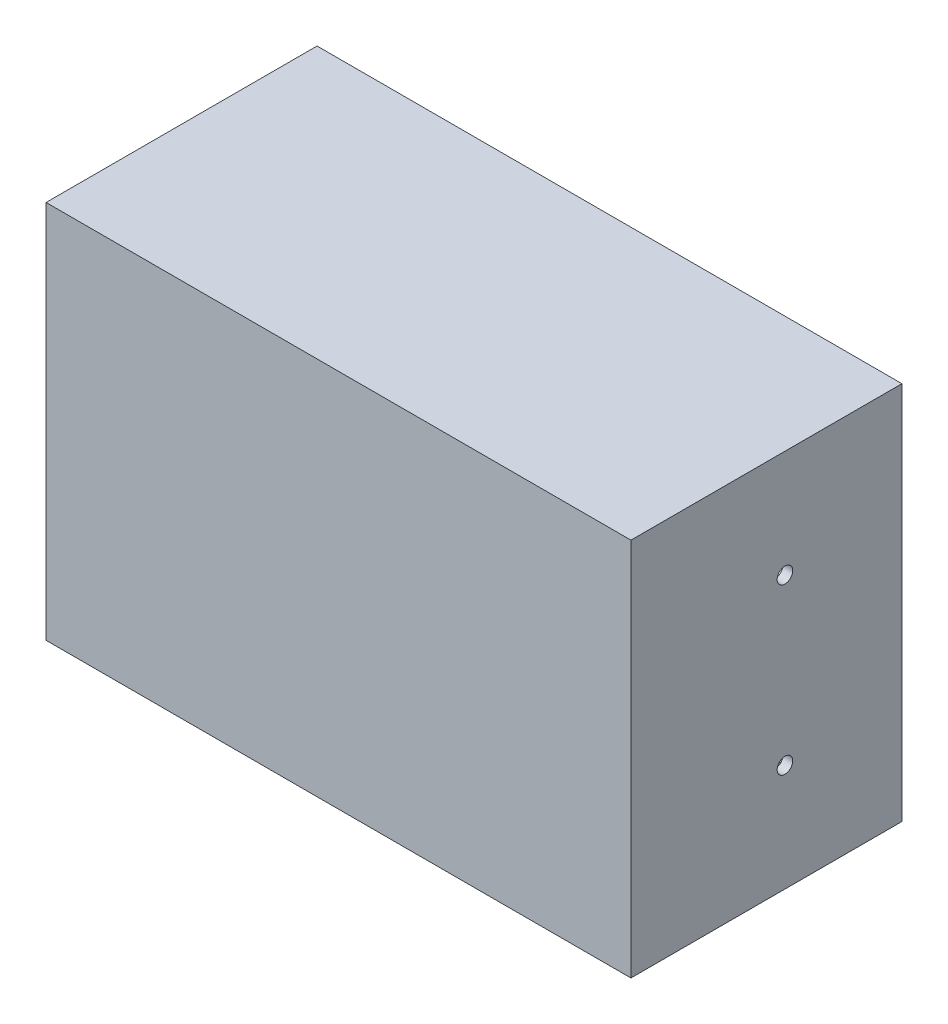
SolidWorks part; units mm, degrees
ref_plane "Ebene vorne" through (0, 0, 0) normal (0, 0, 1) x (1, 0, 0)
ref_plane "Ebene oben" through (0, 0, 0) normal (0, 1, 0) x (1, 0, 0)
ref_plane "Ebene rechts" through (0, 0, 0) normal (1, 0, 0) x (0, 0, -1)
sketch "Skizze1" plane through (0, 0, 0) normal (0, 0, 1) x (1, 0, 0)
  line L1 (-150, -97.25) -> (150, -97.25)
  line L2 (-150, -97.25) -> (-150, 97.25)
  line L3 (-150, 97.25) -> (150, 97.25)
  line L4 (150, -97.25) -> (150, 97.25)
  line L5 (-150, -97.25) -> (150, 97.25) construction
  line L6 (-150, 97.25) -> (150, -97.25) construction
  point P0 (0, 0)
  dimension "D1" = 194.5
  dimension "D2" = 300
extrude "Aufsatz-Linear austragen1" add sketch "Skizze1" along normal blind 139 contours L3 L4 L1 L2
sketch "Skizze2" plane through (0, 0, 0) normal (0, 0, -1) x (-1, 0, 0)
  line L0 (150, 97.25) -> (-150, 97.25) construction
  line L1 (-145, 92.25) -> (145, 92.25)
  line L2 (-145, 92.25) -> (-145, -92.25)
  line L3 (-145, -92.25) -> (145, -92.25)
  line L4 (145, 92.25) -> (145, -92.25)
  line L5 (-145, 92.25) -> (145, -92.25) construction
  line L6 (-145, -92.25) -> (145, 92.25) construction
  line L7 (150, -97.25) -> (150, 97.25) construction
  line L8 (150, -97.25) -> (-150, -97.25) construction
  line L9 (-150, -97.25) -> (-150, 97.25) construction
  point P0 (0, 0)
  dimension "D1" = 5
  dimension "D2" = 5
  dimension "D3" = 5
  dimension "D4" = 5
extrude "Schnitt-Linear austragen1" cut sketch "Skizze2" against normal blind 134 contours L3 L4 L1 L2
sketch "Skizze5" plane through (-150, 0, 0) normal (-1, 0, 0) x (0, 0, 1)
  line L0 (0, -97.25) -> (0, 97.25) construction
  line L1 (139, -97.25) -> (0, -97.25) construction
  circle A0 centre (60, -42.25) radius 28.2128
  dimension "D1" = 60
  dimension "D2" = 55
ref_plane "Ebene1" through (0, 0, 0) normal (1, 0, 0) x (0, 0, -1)
ref_plane "Ebene2" through (0, 0, 0) normal (0, 1, 0) x (1, 0, 0)
hole_wizard "Ø8.0mm Stiftloch1" positions "Skizze7" profile "Skizze6" hole size "Ø8.0" standard "ANSI Metrisch" end condition through all
sketch "Skizze7" plane through (-150, 0, 0) normal (-1, 0, 0) x (0, 0, 1)
  point P0 (60, -42.25)
sketch "Skizze6" plane through (-150, -42.25, 60) normal (0, 1, 0) x (0, 0, 1)
  line L0 (0, 0) -> (0, 300)
  line L1 (0, 300) -> (4, 300)
  line L2 (4, 300) -> (4, 0)
  line L5 (4, 0) -> (0, 0)
  line L11 (0, -6.35) -> (0, 107.95) construction
  dimension "Bohrerdurchmesser" = 8
  dimension "Bohrungstiefe" = 300
mirror "Spiegeln1" about plane through (0, 0, 0) normal (0, 1, 0) of "Ø8.0mm Stiftloch1"
ref_plane "Ebene3" through (0, 0, 30) normal (0, 0, -1) x (-1, 0, 0)
sketch "Skizze8" plane through (0, 0, 30) normal (0, 0, -1) x (-1, 0, 0)
  line L0 (-145, 92.25) -> (145, 92.25)
  line L1 (-145, 92.25) -> (-145, -92.25)
  line L2 (145, 92.25) -> (145, -92.25)
  line L3 (-145, -92.25) -> (145, -92.25)
  line L4 (125, -72.25) -> (-125, -72.25)
  line L5 (125, -72.25) -> (125, 72.25)
  line L6 (125, 72.25) -> (-125, 72.25)
  line L7 (-125, -72.25) -> (-125, 72.25)
  line L8 (125, -72.25) -> (-125, 72.25) construction
  line L9 (125, 72.25) -> (-125, -72.25) construction
  line L10 (-145, -92.25) -> (145, -92.25) construction
  line L11 (-145, 92.25) -> (145, 92.25) construction
  line L12 (-145, 92.25) -> (-145, -92.25) construction
  line L13 (145, 92.25) -> (145, -92.25) construction
  point P0 (0, 0)
  dimension "D1" = 20
  dimension "D2" = 20
  dimension "D3" = 20
  dimension "D4" = 20
extrude "Aufsatz-Linear austragen2" add sketch "Skizze8" along normal blind 25
sketch "Skizze9" plane through (0, 0, 30) normal (0, 0, -1) x (-1, 0, 0)
  line L1 (-145, -92.25) -> (-125, -92.25)
  line L2 (-145, -92.25) -> (-145, -72.25)
  line L3 (-145, -72.25) -> (-125, -72.25)
  line L4 (-125, -92.25) -> (-125, -72.25)
extrude "Aufsatz-Linear austragen3" add sketch "Skizze9" against normal up to next
sketch "Skizze12" plane through (0, 0, 5) normal (0, 0, -1) x (-1, 0, 0)
  line L0 (-145, -92.25) -> (145, -92.25) construction
  line L1 (-125, -72.25) -> (125, -72.25) construction
  line L2 (-145, 92.25) -> (-145, -92.25) construction
  circle A0 centre (-135, -82.25) radius 10
hole_wizard "Kernloch für M4x0.71" positions "Skizze14" profile "Skizze15" hole size "M4x0.7" standard "ANSI Metrisch"
sketch "Skizze14" plane through (0, 0, 5) normal (0, 0, -1) x (-1, 0, 0)
  point P0 (-135, -82.25)
sketch "Skizze15" plane through (135, -82.25, 5) normal (1, 0, 0) x (0, 1, 0)
  line L0 (0, 0) -> (0, 20.9914)
  line L1 (0, 20.9914) -> (1.65, 20)
  line L2 (1.65, 20) -> (1.65, 0)
  line L5 (1.65, 0) -> (0, 0)
  line L10 (0, 20.9914) -> (-1.65, 20) construction
  line L11 (0, -6.35) -> (0, 107.95) construction
  dimension "Bohrerdurchmesser" = 3.3
  dimension "Bohrungstiefe" = 20
  dimension "Spitzenwinkel" = 118
mirror "Spiegeln4" about plane through (0, 0, 0) normal (0, 1, 0) of "Aufsatz-Linear austragen3", "Kernloch für M4x0.71"
mirror "Spiegeln5" about plane through (0, 0, 0) normal (1, 0, 0) of "Spiegeln4", "Aufsatz-Linear austragen3", "Kernloch für M4x0.71"
sketch "Skizze16" plane through (0, 0, 134) normal (0, 0, -1) x (-1, 0, 0)
  line L1 (-125, 72.25) -> (125, 72.25)
  line L2 (-125, 72.25) -> (-125, -72.25)
  line L3 (-125, -72.25) -> (125, -72.25)
  line L4 (125, 72.25) -> (125, -72.25)
  line L5 (-145, 92.25) -> (145, 92.25)
  line L6 (-145, 92.25) -> (-145, -92.25)
  line L7 (-145, -92.25) -> (145, -92.25)
  line L8 (145, 92.25) -> (145, -92.25)
extrude "Aufsatz-Linear austragen4" add sketch "Skizze16" along normal blind 20
